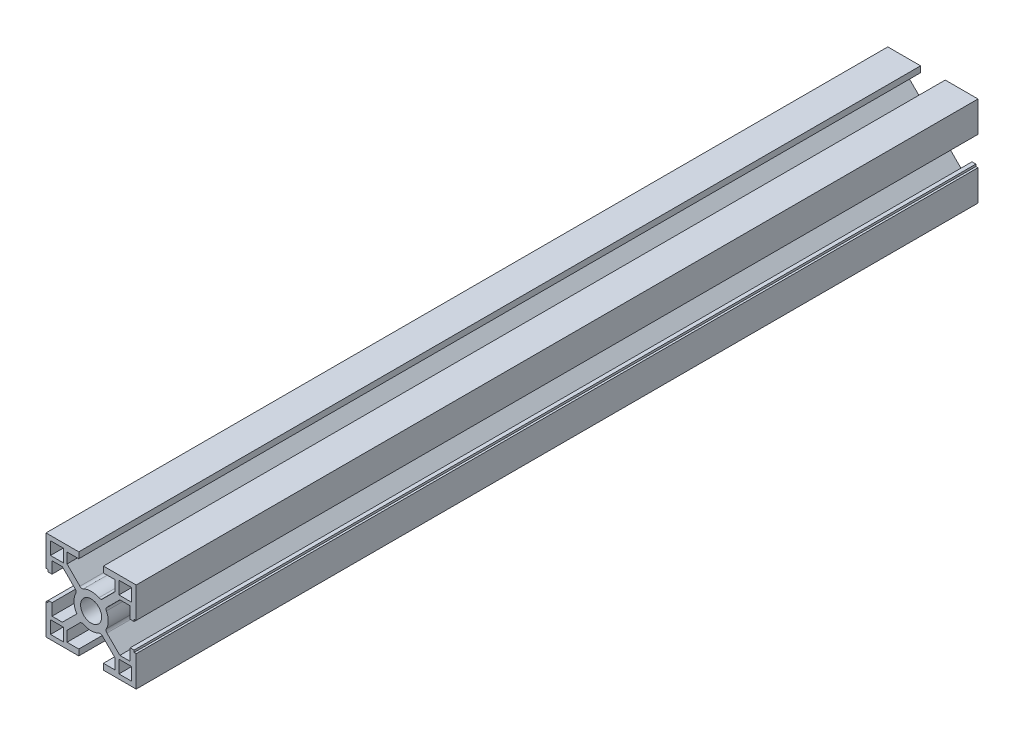
SolidWorks part; units mm, degrees
material "6063-O"
ref_plane "Front Plane" through (0, 0, 0) normal (0, 0, 1) x (1, 0, 0)
ref_plane "Top Plane" through (0, 0, 0) normal (0, 1, 0) x (1, 0, 0)
ref_plane "Right Plane" through (0, 0, 0) normal (1, 0, 0) x (0, 0, -1)
sketch "Sketch1" plane through (0, 0, 0) normal (0, 0, 1) x (1, 0, 0)
  line L0 (-13, 8) -> (-9.5556, 8)
  line L1 (-15, -15) -> (-4.1, -15)
  line L2 (-15, -15) -> (-15, -4.8)
  line L3 (-15, 15) -> (-4.1, 15)
  line L4 (15, -15) -> (15, -4.8)
  line L5 (-15, -15) -> (15, 15) construction
  line L6 (-15, 15) -> (15, -15) construction
  line L7 (-8, 9.5556) -> (-8, 13)
  line L8 (-8, 9.5556) -> (-3.7211, 5.2767)
  line L9 (-9.5556, 8) -> (-5.2767, 3.7211)
  line L10 (13.5, 13.5) -> (13.5, 9.25)
  line L11 (-13.5, -9.25) -> (-9.25, -9.25)
  line L12 (-13, -8) -> (-13, -4.1)
  line L13 (13, 8) -> (9.5556, 8)
  line L14 (8, 13) -> (8, 9.5556)
  line L15 (-14.3, -4.1) -> (-13, -4.1)
  line L16 (15, 4.8) -> (15, 15)
  line L17 (13, -8) -> (9.5556, -8)
  line L18 (8, -13) -> (8, -9.5556)
  line L19 (-14.3, 4.1) -> (-13, 4.1)
  line L20 (15, -15) -> (15, 15) construction
  line L21 (-13, -8) -> (-9.5556, -8)
  line L22 (-8, -13) -> (-8, -9.5556)
  line L23 (4.1, 15) -> (15, 15)
  line L24 (13, 4.1) -> (13, 8)
  line L25 (14.3, -4.1) -> (13, -4.1)
  line L26 (3.7211, 5.2767) -> (8, 9.5556)
  line L27 (14.3, 4.1) -> (13, 4.1)
  line L28 (-15, 15) -> (15, 15) construction
  line L29 (4.1, 13) -> (8, 13)
  line L30 (-13, 13) -> (13, 13) construction
  line L31 (3.7211, -5.2767) -> (8, -9.5556)
  line L32 (-4.1, 15) -> (-4.1, 13)
  line L33 (4.1, -13) -> (8, -13)
  line L34 (4.1, 15) -> (4.1, 13)
  line L35 (-13, -13) -> (13, -13) construction
  line L36 (5.2767, -3.7211) -> (9.5556, -8)
  line L37 (5.2767, 3.7211) -> (9.5556, 8)
  line L38 (-4.1, -13) -> (-4.1, -15)
  line L39 (-9.5556, -8) -> (-4.7326, -3.1769)
  line L40 (4.1, -13) -> (4.1, -15)
  line L41 (-8, -9.5556) -> (-3.7211, -5.2767)
  line L42 (-13.5, -9.25) -> (-13.5, -13.5)
  line L43 (-8, 13) -> (-4.1, 13)
  line L44 (13, -8) -> (13, -4.1)
  line L45 (-8, -13) -> (-4.1, -13)
  line L46 (-15, 4.8) -> (-15, 15)
  line L47 (-15, -15) -> (-15, 15) construction
  line L48 (13, -13) -> (13, 13) construction
  line L49 (-13, 4.1) -> (-13, 8)
  line L50 (-13, -13) -> (-13, 13) construction
  line L51 (4.1, -15) -> (15, -15)
  line L52 (-15, -15) -> (15, -15) construction
  line L53 (-13.5, -13.5) -> (-9.25, -13.5)
  line L54 (-9.25, -9.25) -> (-9.25, -13.5)
  line L55 (9.25, 9.25) -> (13.5, 9.25)
  line L56 (9.25, 13.5) -> (13.5, 13.5)
  line L57 (9.25, 13.5) -> (9.25, 9.25)
  line L58 (13.5, -13.5) -> (9.25, -13.5)
  line L59 (-9.25, 13.5) -> (-13.5, 13.5)
  line L60 (-9.25, 13.5) -> (-9.25, 9.25)
  line L61 (-9.25, 9.25) -> (-13.5, 9.25)
  line L62 (-13.5, 13.5) -> (-13.5, 9.25)
  line L63 (13.5, -9.25) -> (13.5, -13.5)
  line L64 (13.5, -9.25) -> (9.25, -9.25)
  line L65 (9.25, -9.25) -> (9.25, -13.5)
  line L69 (15, -4.8) -> (14.3, -4.8)
  line L70 (14.3, -4.1) -> (14.3, -4.8)
  line L73 (15, 4.8) -> (14.3, 4.8)
  line L74 (14.3, 4.1) -> (14.3, 4.8)
  line L77 (-15, -4.8) -> (-14.3, -4.8)
  line L78 (-14.3, -4.1) -> (-14.3, -4.8)
  line L81 (-15, 4.8) -> (-14.3, 4.8)
  line L82 (-14.3, 4.1) -> (-14.3, 4.8)
  circle A0 centre (0, 0) radius 3.5
  arc A1 (2.5641, 5.0907) -> (-2.5641, 5.0907) centre (0, 0) ccw
  arc A2 (5.0907, -2.5641) -> (5.0907, 2.5641) centre (0, 0) ccw
  arc A3 (-2.5641, -5.0907) -> (2.5641, -5.0907) centre (0, 0) ccw
  arc A4 (-5.0907, 2.5641) -> (-4.7326, -3.1769) centre (0, 0) ccw
  arc A5 (-5.2767, 3.7211) -> (-5.0907, 2.5641) centre (-5.9838, 3.014) cw
  arc A6 (-3.7211, 5.2767) -> (-2.5641, 5.0907) centre (-3.014, 5.9838) ccw
  arc A7 (5.2767, 3.7211) -> (5.0907, 2.5641) centre (5.9838, 3.014) ccw
  arc A8 (3.7211, 5.2767) -> (2.5641, 5.0907) centre (3.014, 5.9838) cw
  arc A9 (5.2767, -3.7211) -> (5.0907, -2.5641) centre (5.9838, -3.014) cw
  arc A10 (3.7211, -5.2767) -> (2.5641, -5.0907) centre (3.014, -5.9838) ccw
  arc A11 (-3.7211, -5.2767) -> (-2.5641, -5.0907) centre (-3.014, -5.9838) cw
  point P0 (0, 0)
  point P29 (-15, 0)
  point P34 (15, 0)
  point P39 (0, 15)
  point P44 (0, -15)
  point P55 (-4.7326, 3.1769)
  point P91 (4.7326, -3.1769)
  point P96 (-3.1769, -4.7326)
  dimension "D1" = 7
  dimension "D2" = 11.4
  dimension "D34" = 1
  dimension "D3" = 30
  dimension "D4" = 30
  dimension "D5" = 7
  dimension "D6" = 7
  dimension "D7" = 7
  dimension "D8" = 7
  dimension "D9" = 1.5
  dimension "D10" = 1.5
  dimension "D11" = 4.25
  dimension "D12" = 4.25
  dimension "D13" = 4.25
  dimension "D14" = 8.2
  dimension "D15" = 4.25
  dimension "D16" = 1.5
  dimension "D18" = 10.9
  dimension "D19" = 10.9
  dimension "D20" = 10.9
  dimension "D21" = 10.9
  dimension "D22" = 10.9
  dimension "D23" = 10.9
  dimension "D24" = 10.9
  dimension "D25" = 1.5
  dimension "D26" = 0.7
  dimension "D27" = 0.7
  dimension "D28" = 0.7
  dimension "D29" = 0.7
  dimension "D30" = 0.7
  dimension "D31" = 0.7
  dimension "D32" = 0.7
  dimension "D33" = 0.7
  dimension "D17" = 2
extrude "Boss-Extrude1" add sketch "Sketch1" along normal mid plane 280
